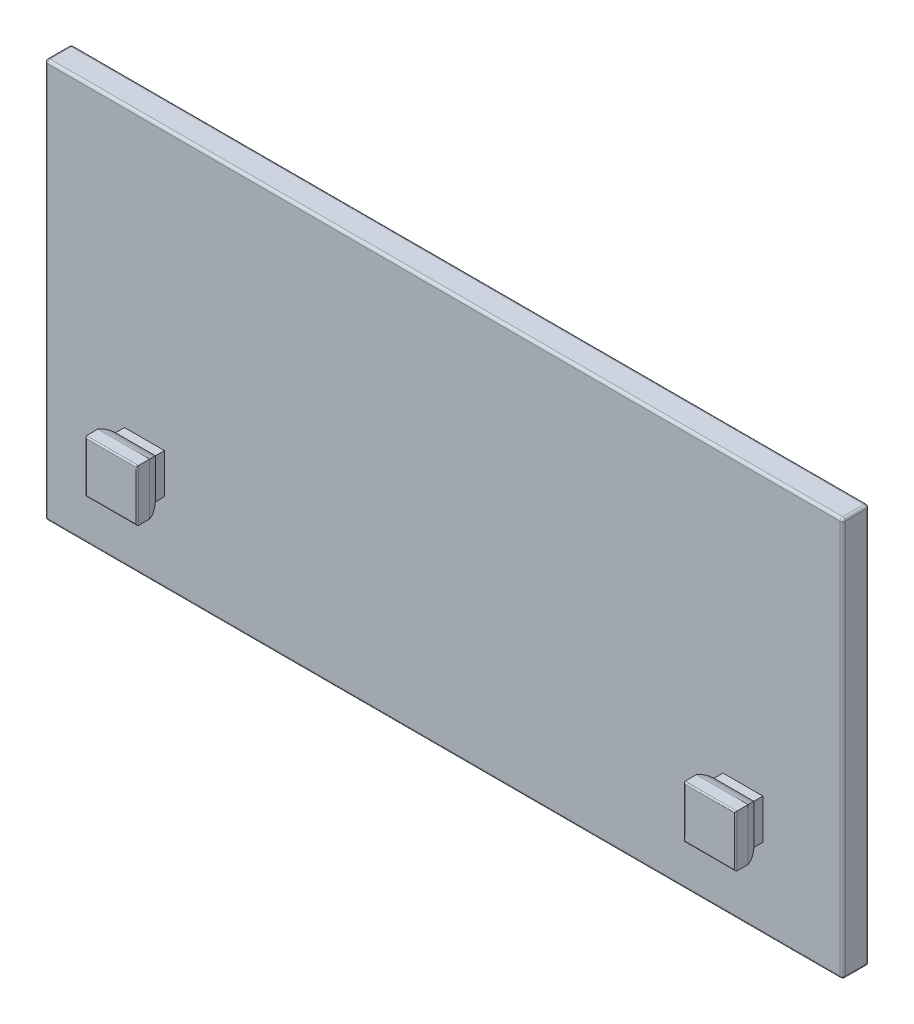
SolidWorks part; units mm, degrees
ref_plane "前视基准面" through (0, 0, 0) normal (0, 0, 1) x (1, 0, 0)
ref_plane "上视基准面" through (0, 0, 0) normal (0, 1, 0) x (1, 0, 0)
ref_plane "右视基准面" through (0, 0, 0) normal (1, 0, 0) x (0, 0, -1)
sketch "草图1" plane through (0, 0, 0) normal (0, 0, 1) x (1, 0, 0)
  line L1 (-30, -7.5) -> (30, -7.5)
  line L2 (-30, -7.5) -> (-30, 22.5)
  line L3 (-30, 22.5) -> (30, 22.5)
  line L4 (30, -7.5) -> (30, 22.5)
extrude "凸台-拉伸1" add sketch "草图1" against normal blind 2
sketch "草图2" plane through (0, 0, 0) normal (0, 0, 1) x (1, 0, 0)
  line L1 (-24, -1.5) -> (-21, -1.5)
  line L2 (-24, -1.5) -> (-24, 1.5)
  line L3 (-24, 1.5) -> (-21, 1.5)
  line L4 (-21, -1.5) -> (-21, 1.5)
extrude "凸台-拉伸2" add sketch "草图2" along normal blind 1
sketch "草图3" plane through (0, -1.5, 0) normal (0, -1, 0) x (1, 0, 0)
  line L0 (-24.45, 2.5) -> (-20.55, 2.5)
  line L1 (-24.45, 2.5) -> (-24.45, 1.5556)
  line L3 (-20.55, 2.5) -> (-20.55, 1.5556)
  line L5 (-24, 1) -> (-24, 0) construction
  line L6 (-24, 0.6771) -> (-21, 0.6771)
  arc A0 (-21, 0.6771) -> (-20.55, 1.5556) centre (-22.5, 2) ccw
  arc A1 (-24.45, 1.5556) -> (-24, 0.6771) centre (-22.5, 2) ccw
extrude "凸台-拉伸3" add sketch "草图3" along normal blind 1 and the other way blind 4
sketch "草图4" plane through (-24.45, 0, 0) normal (-1, 0, 0) x (0, 0, 1)
  line L0 (2.5, 1.95) -> (1.5556, 1.95)
  line L1 (0.6771, -2.5) -> (2.5, -2.5)
  line L2 (0.6771, -2.5) -> (0.6771, -1.5)
  line L3 (0.6771, 2.5) -> (2.5, 2.5)
  line L4 (2.5, -2.5) -> (2.5, -1.95)
  line L5 (2.5, -1.95) -> (1.5556, -1.95)
  line L7 (0.6771, 1.5) -> (0.6771, 2.5)
  line L8 (2.5, 1.95) -> (2.5, 2.5)
  arc A2 (0.6771, -1.5) -> (1.5556, -1.95) centre (2, 0) ccw
  arc A3 (1.5556, 1.95) -> (0.6771, 1.5) centre (2, 0) ccw
extrude "切除-拉伸1" cut sketch "草图4" against normal up to next
mirror "镜向1" about plane through (0, 0, 0) normal (1, 0, 0) of "凸台-拉伸2", "凸台-拉伸3", "切除-拉伸1"
fillet "圆角1" radius 0.1 8 edges at (24.45, 0, 2.5) (22.5, -1.95, 2.5) (20.55, 0, 2.5) (22.5, 1.95, 2.5) (-20.55, 0, 2.5) (-22.5, -1.95, 2.5) (-24.45, 0, 2.5) (-22.5, 1.95, 2.5)
fillet "圆角2" radius 0.2 12 edges at (0, -7.5, -2) (0, -7.5, 0) (-30, -7.5, -1) (-30, 7.5, -2) (-30, 7.5, 0) (30, 7.5, -2) (30, -7.5, -1) (30, 7.5, 0) (-30, 22.5, -1) (0, 22.5, -2) (30, 22.5, -1) (0, 22.5, 0)
